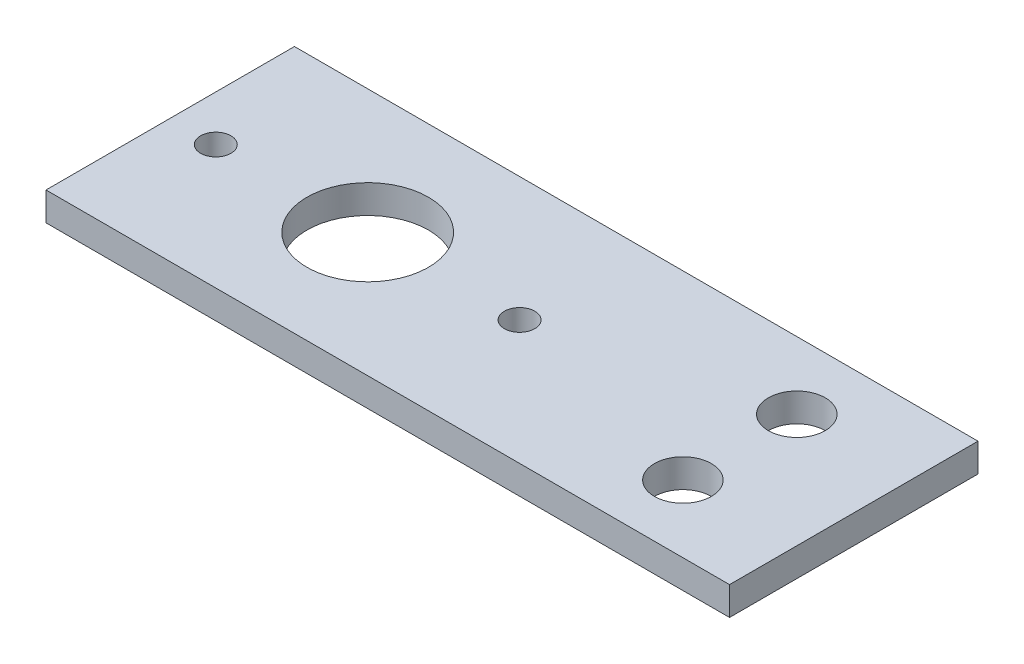
SolidWorks part; units mm, degrees
ref_plane "Front Plane" through (0, 0, 0) normal (0, 0, 1) x (1, 0, 0)
ref_plane "Top Plane" through (0, 0, 0) normal (0, 1, 0) x (1, 0, 0)
ref_plane "Right Plane" through (0, 0, 0) normal (1, 0, 0) x (0, 0, -1)
sketch "Sketch3" plane through (0, 0, 0) normal (0, 1, 0) x (1, 0, 0)
  line L0 (-114.3, 38.5278) -> (-114.3, -46.6771) construction
  line L1 (-114.3, -20.774) -> (0, -20.774)
  line L2 (-114.3, -20.774) -> (-114.3, 20.774)
  line L3 (-114.3, 20.774) -> (0, 20.774)
  line L5 (0, 20.774) -> (0, -20.774) construction
  line L6 (-114.3, 0) -> (228.6, 0) construction
  line L7 (-114.3, 38.5278) -> (-48.26, 38.5278) construction
  line L8 (-48.26, 38.5278) -> (-48.26, -48.4673) construction
  line L9 (-81.28, 38.5278) -> (-81.28, -48.4673) construction
  line L10 (0, 20.774) -> (0, -20.774)
  circle A0 centre (-106.68, 0) radius 2.54
  circle A1 centre (-81.28, 0) radius 10.16
  circle A2 centre (-55.88, 0) radius 2.54
  circle A4 centre (-19.05, 9.525) radius 4.7625
  circle A5 centre (-19.05, -9.525) radius 4.7625
  point P0 (0, 0)
  point P1 (-19.05, 9.9067)
  dimension "D4" = 20.32
  dimension "D6" = 5.08
  dimension "D2" = 19.05
  dimension "D1" = 114.3
  dimension "D3" = 50.8
  dimension "D5" = 25.4
  dimension "D7" = 66.04
  dimension "D8" = 33.02
  dimension "D9" = 19.05
extrude "Boss-Extrude1" add sketch "Sketch3" along normal blind 4.7625
